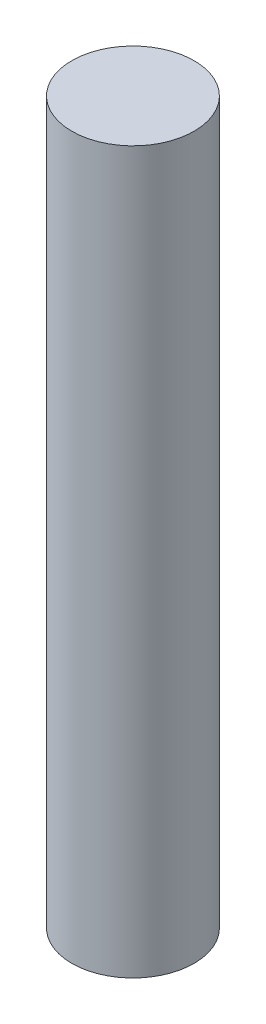
SolidWorks part; units mm, degrees
ref_plane "前视基准面" through (0, 0, 0) normal (0, 0, 1) x (1, 0, 0)
ref_plane "上视基准面" through (0, 0, 0) normal (0, 1, 0) x (1, 0, 0)
ref_plane "右视基准面" through (0, 0, 0) normal (1, 0, 0) x (0, 0, -1)
other "Configuration Table"
sketch "草图1" plane through (0, 0, 0) normal (0, 1, 0) x (1, 0, 0)
  circle A0 centre (0, 0) radius 1.4
  point P0 (-90.6464, 22.0667)
  dimension "D1" = 2.8
extrude "凸台-拉伸1" add sketch "草图1" along normal blind 16.5
